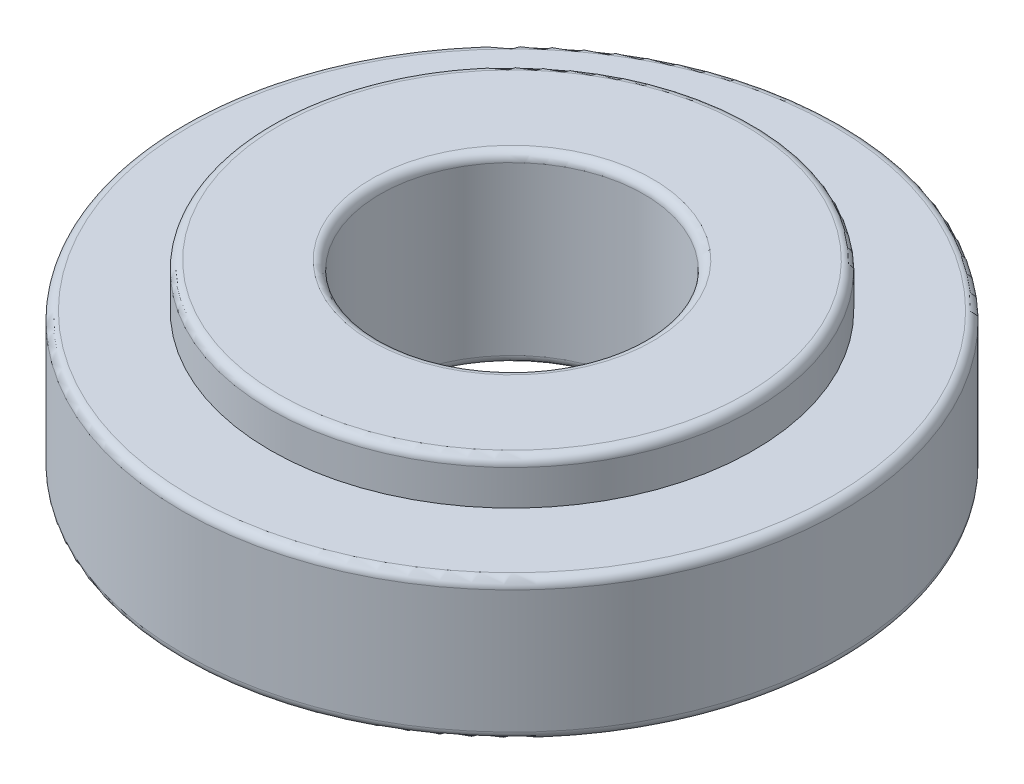
SolidWorks part; units mm, degrees
ref_plane "前视基准面" through (0, 0, 0) normal (0, 0, 1) x (1, 0, 0)
ref_plane "上视基准面" through (0, 0, 0) normal (0, 1, 0) x (1, 0, 0)
ref_plane "右视基准面" through (0, 0, 0) normal (1, 0, 0) x (0, 0, -1)
sketch "草图1" plane through (0, 0, 0) normal (0, 1, 0) x (1, 0, 0)
  circle A0 centre (0, 0) radius 3.75
  circle A1 centre (0, 0) radius 1.5
  dimension "D1" = 3
  dimension "D2" = 7.5
extrude "凸台-拉伸2" add sketch "草图1" along normal blind 1.6 contours A0
sketch "草图2" plane through (0, 1.6, 0) normal (0, 1, 0) x (1, 0, 0)
  circle A0 centre (0, 0) radius 1.5
extrude "切除-拉伸1" cut sketch "草图2" against normal blind 2
sketch "草图3" plane through (0, 1.6, 0) normal (0, 1, 0) x (1, 0, 0)
  circle A0 centre (0, 0) radius 2.75
  dimension "D1" = 5.5
extrude "凸台-拉伸3" add sketch "草图3" along normal blind 0.5
sketch "草图4" plane through (0, 2.1, 0) normal (0, 1, 0) x (1, 0, 0)
  circle A0 centre (0, 0) radius 1.5
extrude "切除-拉伸2" cut sketch "草图4" against normal blind 3
fillet "圆角1" radius 0.1 5 edges at (0, 0, 3.75) (0, 1.6, 3.75) (0, 2.1, 1.5) (0, 0, 1.5) (0, 2.1, 2.75)
